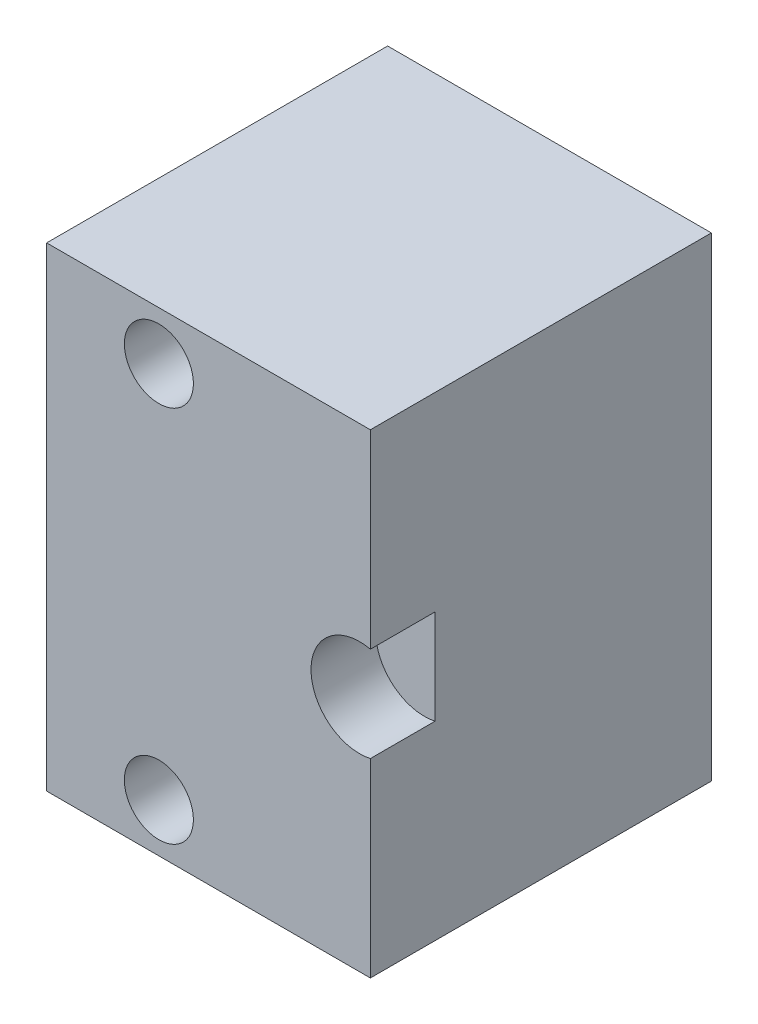
SolidWorks part; units mm, degrees
ref_plane "Спереди" through (0, 0, 0) normal (0, 0, 1) x (1, 0, 0)
ref_plane "Сверху" through (0, 0, 0) normal (0, 1, 0) x (1, 0, 0)
ref_plane "Справа" through (0, 0, 0) normal (1, 0, 0) x (0, 0, -1)
sketch "Эскиз1" plane through (0, 0, 0) normal (0, 0, 1) x (1, 0, 0)
  line L0 (5.2, 19.75) -> (5.2, 2.25) construction
  line L1 (0, 22) -> (15, 22)
  line L2 (0, 22) -> (0, 0)
  line L3 (0, 0) -> (15, 0)
  line L4 (15, 22) -> (15, 0)
  circle A0 centre (5.2, 19.75) radius 1.6
  circle A1 centre (5.2, 2.25) radius 1.6
  point P0 (0, 0)
  point P10 (5.2, 11)
  point P11 (0, 11)
  dimension "D1" = 3.2
  dimension "D2" = 17.5
  dimension "D4" = 15
  dimension "D5" = 5.2
  dimension "D6" = 22
extrude "Бобышка-Вытянуть1" add sketch "Эскиз1" along normal blind 15.8
sketch "Эскиз2" plane through (0, 0, 15.8) normal (0, 0, 1) x (1, 0, 0)
  line L0 (0, 22) -> (0, 0) construction
  circle A0 centre (14.5, 11) radius 2.25
  point P4 (0, 0)
  point P5 (0, 11)
  dimension "D1" = 4.5
  dimension "D2" = 14.5
extrude "Вырез-Вытянуть1" cut sketch "Эскиз2" against normal blind 3
